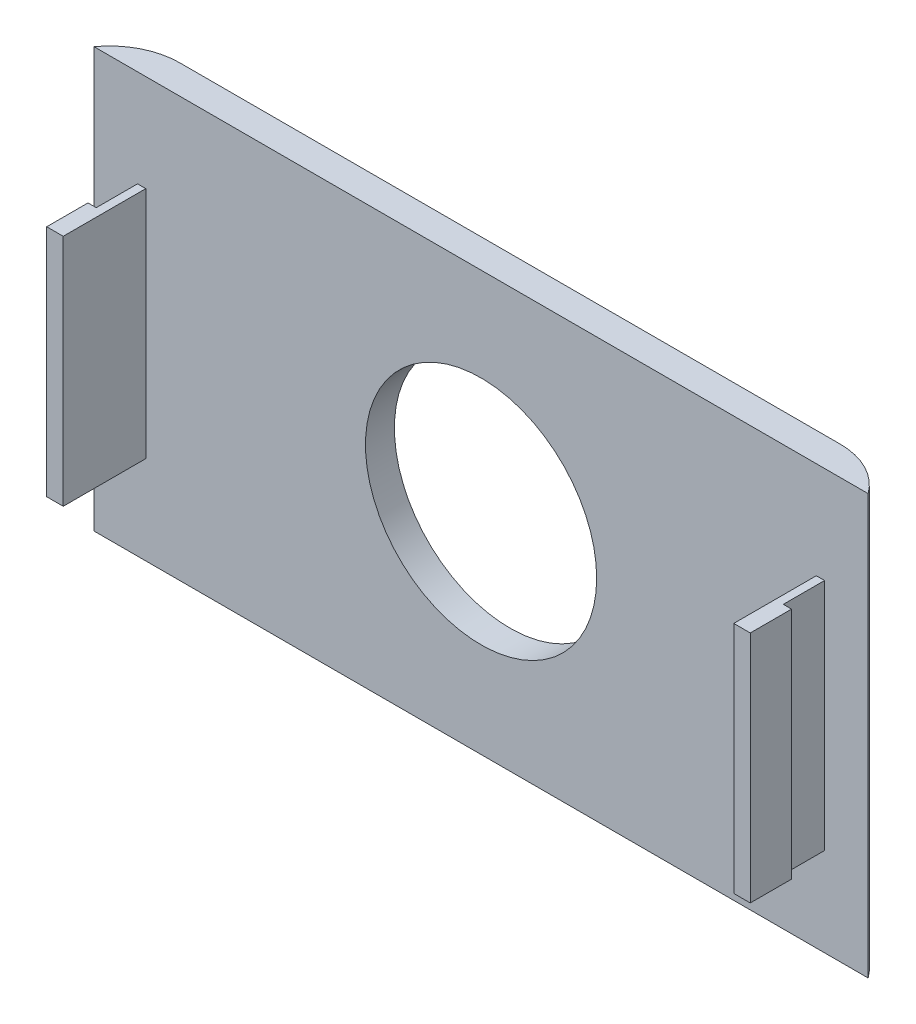
SolidWorks part; units mm, degrees
ref_plane "Front Plane" through (0, 0, 0) normal (0, 0, 1) x (1, 0, 0)
ref_plane "Top Plane" through (0, 0, 0) normal (0, 1, 0) x (1, 0, 0)
ref_plane "Right Plane" through (0, 0, 0) normal (1, 0, 0) x (0, 0, -1)
sketch "Sketch1" plane through (0, 0, 0) normal (0, 1, 0) x (1, 0, 0)
  line L0 (-46.8746, -10.751) -> (46.8746, -10.751)
  line L1 (-40, -7.25) -> (40, -7.25)
  line L5 (0, 16.8687) -> (0, -34.2856) construction
  arc A0 (46.8746, -10.751) -> (40, -7.25) centre (40, -15.75) ccw
  arc A1 (-46.8746, -10.751) -> (-40, -7.25) centre (-40, -15.75) cw
  point P4 (0, -10.751)
  point P10 (0, -7.25)
  point P20 (0, -17.75)
  point P21 (0, 0)
extrude "Boss-Extrude1" add sketch "Sketch1" along normal blind 50.8
sketch "Sketch4" plane through (0, 0, 10.751) normal (0, 0, 1) x (1, 0, 0)
  line L1 (40.6, 39.0508) -> (42.6, 39.0508)
  line L2 (40.6, 39.0508) -> (40.6, 10.7315)
  line L3 (40.6, 10.7315) -> (42.6, 10.7315)
  line L4 (42.6, 39.0508) -> (42.6, 10.7315)
extrude "Boss-Extrude2" add sketch "Sketch4" along normal blind 10
sketch "Sketch5" plane through (42.6, 0, 0) normal (1, 0, 0) x (0, 0, -1)
  line L0 (-20.751, 39.0508) -> (-10.751, 39.0508) construction
  line L1 (-15.751, 39.0508) -> (-10.751, 39.0508)
  line L2 (-15.751, 39.0508) -> (-15.751, 10.7315)
  line L3 (-15.751, 10.7315) -> (-10.751, 10.7315)
  line L4 (-10.751, 39.0508) -> (-10.751, 10.7315)
extrude "Cut-Extrude2" cut sketch "Sketch5" against normal blind 1
sketch "Sketch6" plane through (0, 50.8, 0) normal (0, 1, 0) x (1, 0, 0)
  line L0 (0, -10.751) -> (0, -21.5299) construction
  line L1 (-46.8746, -10.751) -> (46.8746, -10.751) construction
  point P5 (2.5073, -500000)
sketch "Sketch7" plane through (0, 0, 10.751) normal (0, 0, 1) x (1, 0, 0)
  line L0 (0, 0) -> (0, 50.3865) construction
ref_plane "Plane1" through (0, 0, 0) normal (1, 0, 0) x (0, 0, -1)
mirror "Mirror1" about plane through (0, 0, 0) normal (1, 0, 0) of "Cut-Extrude2", "Boss-Extrude2"
sketch "Sketch8" plane through (0, 0, 10.751) normal (0, 0, 1) x (1, 0, 0)
  circle A0 centre (0, 25.5) radius 14
extrude "Cut-Extrude3" cut sketch "Sketch8" against normal through all
